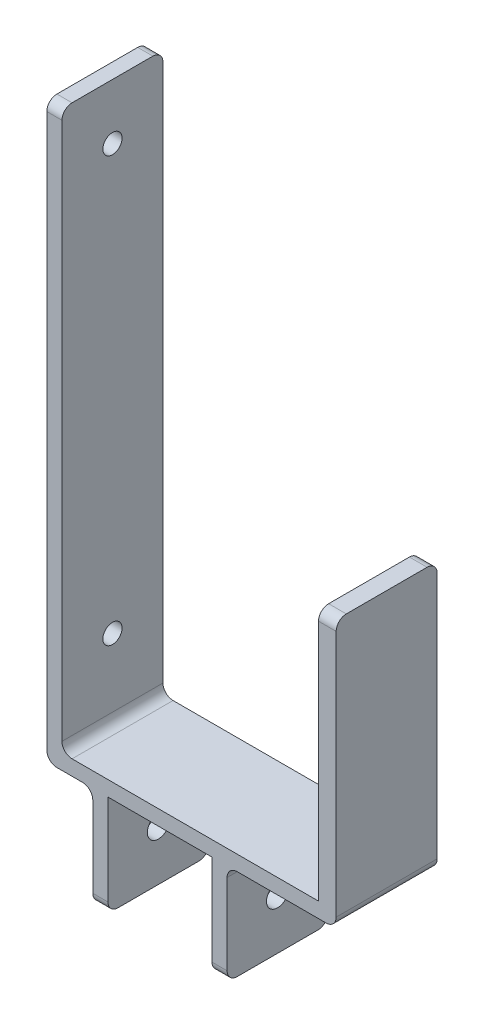
SolidWorks part; units mm, degrees
material "ABS"
ref_plane "Front Plane" through (0, 0, 0) normal (0, 0, 1) x (1, 0, 0)
ref_plane "Top Plane" through (0, 0, 0) normal (0, 1, 0) x (1, 0, 0)
ref_plane "Right Plane" through (0, 0, 0) normal (1, 0, 0) x (0, 0, -1)
sketch "Sketch1" plane through (0, 0, 0) normal (0, 0, 1) x (1, 0, 0)
  line L0 (-25.4, 0) -> (25.4, 0)
  line L1 (25.4, 0) -> (25.4, 50)
  line L2 (25.4, 50) -> (28.9, 50)
  line L3 (28.9, 50) -> (28.9, -3)
  line L4 (28.9, -3) -> (7.3, -3)
  line L5 (-28.4, -3) -> (-28.4, 110.5)
  line L6 (-28.4, 110.5) -> (-25.4, 110.5)
  line L7 (-25.4, 110.5) -> (-25.4, 0)
  line L8 (-19.3, -3) -> (-19.3, -23)
  line L9 (-19.3, -23) -> (-16.3, -23)
  line L10 (-16.3, -23) -> (-16.3, -3)
  line L11 (4.3, -3) -> (4.3, -23)
  line L12 (4.3, -23) -> (7.3, -23)
  line L13 (7.3, -23) -> (7.3, -3)
  line L14 (-19.3, -3) -> (-28.4, -3)
  line L15 (4.3, -3) -> (-16.3, -3)
  dimension "D1" = 57.3
  dimension "D2" = 50.8
  dimension "D3" = 3.5
  dimension "D4" = 50
  dimension "D5" = 110.5
  dimension "D6" = 3
  dimension "D7" = 3
  dimension "D8" = 20.6
  dimension "D9" = 9.1
  dimension "D10" = 20
extrude "Boss-Extrude1" add sketch "Sketch1" along normal blind 20
fillet "Fillet1" radius 2 13 edges at (5.8, -23, 20) (5.8, -23, 0) (-17.8, -23, 0) (-17.8, -23, 20) (-19.3, -3, 10) (7.3, -3, 10) (28.9, -3, 10) (-28.4, -3, 10) (-25.4, 0, 10) (27.15, 50, 0) (27.15, 50, 20) (-26.9, 110.5, 0) (-26.9, 110.5, 20)
sketch "Sketch2" plane through (-28.4, 0, 0) normal (-1, 0, 0) x (0, 0, 1)
  line L0 (10, -13) -> (10, -23) construction
  line L1 (18, -23) -> (2, -23) construction
  line L2 (10, 99.5) -> (10, 110.5) construction
  line L3 (18, 110.5) -> (2, 110.5) construction
  circle A0 centre (10, 99.5) radius 1.9
  circle A1 centre (10, 15.5) radius 1.9
  circle A2 centre (10, -13) radius 2.2
  dimension "D1" = 3.8
  dimension "D2" = 4.4
  dimension "D4" = 84
  dimension "D3" = 10
  dimension "D5" = 11
extrude "Cut-Extrude1" cut sketch "Sketch2" against normal blind 40
